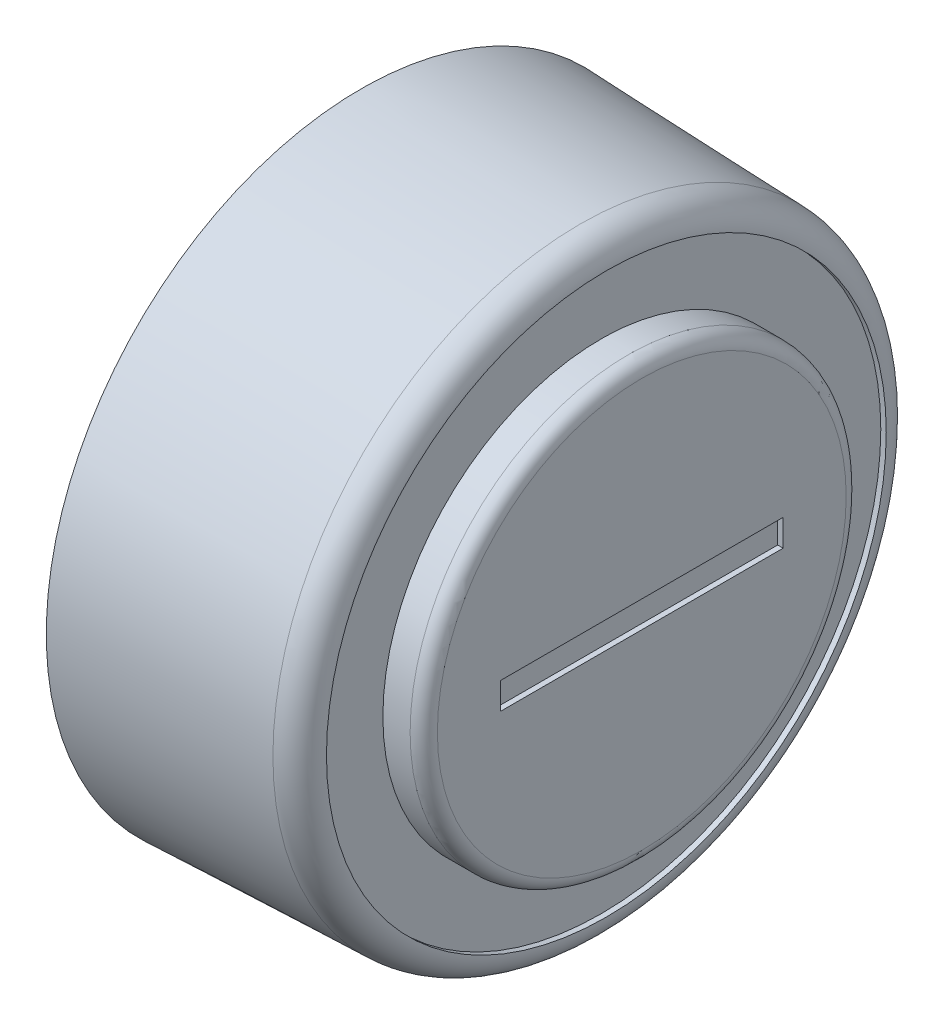
SolidWorks part; units mm, degrees
ref_plane "Front Plane" through (0, 0, 0) normal (0, 0, 1) x (1, 0, 0)
ref_plane "Top Plane" through (0, 0, 0) normal (0, 1, 0) x (1, 0, 0)
ref_plane "Right Plane" through (0, 0, 0) normal (1, 0, 0) x (0, 0, -1)
sketch "Sketch1" plane through (0, 0, 0) normal (1, 0, 0) x (0, 0, -1)
  circle A0 centre (0, 0) radius 5.775
extrude "Boss-Extrude1" add sketch "Sketch1" along normal blind 4.5 draft 2
sketch "Sketch2" plane through (0, 0, 0) normal (-1, 0, 0) x (0, 0, 1)
  circle A0 centre (0, 0) radius 4
  dimension "D1" = 8
extrude "Boss-Extrude2" add sketch "Sketch2" against normal blind 5.15
fillet "Fillet1" radius 0.5 1 edges at (4.5, 0, -5.6179)
fillet "Fillet2" radius 0.25 1 edges at (5.15, 0, 4)
sketch "Sketch3" plane through (4.5, 0, 0) normal (1, 0, 0) x (0, 0, -1)
  circle A0 centre (0, 0) radius 4
  circle A1 centre (0, 0) radius 5.135
extrude "Cut-Extrude1" cut sketch "Sketch3" against normal blind 0.1
sketch "Sketch4" plane through (0, 0, 0) normal (-1, 0, 0) x (0, 0, 1)
  line L1 (-0.2738, -2.5359) -> (0.2738, -2.5359)
  line L2 (-0.2738, -2.5359) -> (-0.2738, -0.2808)
  line L3 (-0.2738, 2.5359) -> (0.2738, 2.5359)
  line L4 (0.2738, -2.5359) -> (0.2738, -0.2808)
  line L7 (-2.4569, 0.2808) -> (-0.2738, 0.2808)
  line L8 (-2.4569, 0.2808) -> (-2.4569, -0.2808)
  line L9 (-2.4569, -0.2808) -> (-0.2738, -0.2808)
  line L10 (2.4569, 0.2808) -> (2.4569, -0.2808)
  line L13 (-0.2738, 0.2808) -> (-0.2738, 2.5359)
  line L14 (0.2738, 0.2808) -> (2.4569, 0.2808)
  line L15 (0.2738, 0.2808) -> (0.2738, 2.5359)
  line L17 (0.2738, -0.2808) -> (2.4569, -0.2808)
  point P0 (0, 0)
  point P6 (0, 0)
extrude "Cut-Extrude2" cut sketch "Sketch4" against normal blind 0.1
sketch "Sketch5" plane through (5.15, 0, 0) normal (1, 0, 0) x (0, 0, -1)
  line L1 (-2.5936, 0.2449) -> (2.5936, 0.2449)
  line L2 (-2.5936, 0.2449) -> (-2.5936, -0.2449)
  line L3 (-2.5936, -0.2449) -> (2.5936, -0.2449)
  line L4 (2.5936, 0.2449) -> (2.5936, -0.2449)
  line L5 (-2.5936, 0.2449) -> (2.5936, -0.2449) construction
  line L6 (-2.5936, -0.2449) -> (2.5936, 0.2449) construction
  point P0 (0, 0)
extrude "Cut-Extrude3" cut sketch "Sketch5" against normal blind 0.1
